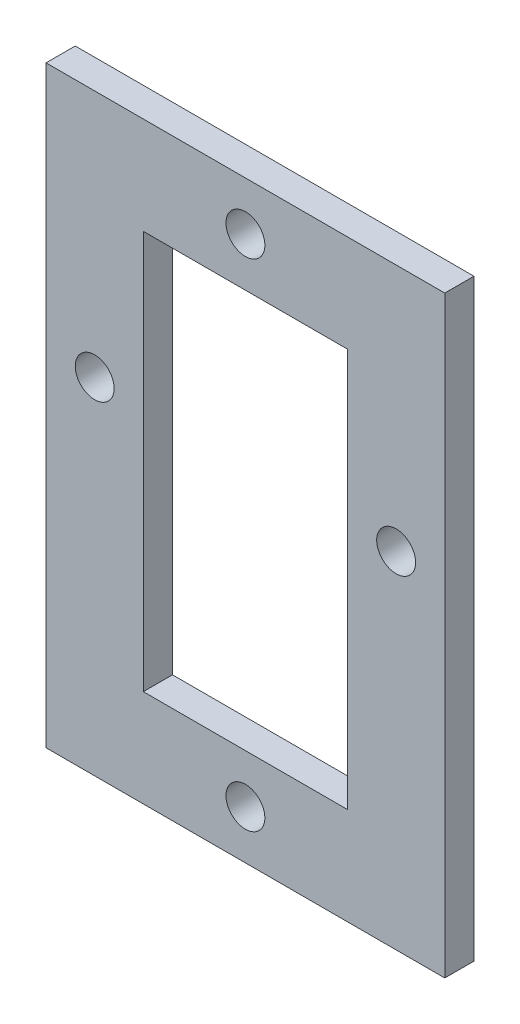
SolidWorks part; units mm, degrees
ref_plane "Front Plane" through (0, 0, 0) normal (0, 0, 1) x (1, 0, 0)
ref_plane "Top Plane" through (0, 0, 0) normal (0, 1, 0) x (1, 0, 0)
ref_plane "Right Plane" through (0, 0, 0) normal (1, 0, 0) x (0, 0, -1)
sketch "Sketch1" plane through (0, 0, 0) normal (0, 0, 1) x (1, 0, 0)
  line L1 (0, 0) -> (41, 0)
  line L2 (0, 0) -> (0, -61)
  line L3 (0, -61) -> (41, -61)
  line L4 (41, 0) -> (41, -61)
  dimension "D1" = 61
  dimension "D2" = 41
extrude "Boss-Extrude1" add sketch "Sketch1" along normal blind 3
sketch "Sketch2" plane through (0, 0, 3) normal (0, 0, 1) x (1, 0, 0)
  line L0 (0, -61) -> (41, -61) construction
  line L1 (10, -10) -> (31, -10)
  line L2 (10, -10) -> (10, -51)
  line L3 (10, -51) -> (31, -51)
  line L4 (31, -10) -> (31, -51)
  line L5 (10, -10) -> (31, -51) construction
  line L6 (10, -51) -> (31, -10) construction
  line L7 (41, -61) -> (41, 0) construction
  point P0 (20.5, -30.5)
  dimension "D1" = 21
  dimension "D2" = 41
  dimension "D3" = 10
  dimension "D4" = 10
extrude "Cut-Extrude1" cut sketch "Sketch2" against normal blind 3
sketch "Sketch3" plane through (0, 0, 3) normal (0, 0, 1) x (1, 0, 0)
  line L0 (0, 0) -> (0, -61) construction
  line L1 (41, -61) -> (41, 0) construction
  line L2 (41, 0) -> (0, 0) construction
  circle A0 centre (36, -25.5) radius 2
  circle A1 centre (5, -25.5) radius 2
  dimension "D1" = 4
  dimension "D2" = 4
  dimension "D3" = 5
  dimension "D4" = 5
  dimension "D6" = 25.5
  dimension "D5" = 25.5
extrude "Cut-Extrude2" cut sketch "Sketch3" against normal blind 3
sketch "Sketch4" plane through (0, 0, 3) normal (0, 0, 1) x (1, 0, 0)
  line L0 (31, -10) -> (10, -10) construction
  line L1 (10, -51) -> (31, -51) construction
  line L2 (41, -61) -> (41, 0) construction
  circle A0 centre (20.5, -5) radius 2
  circle A1 centre (20.5, -56) radius 2
  dimension "D1" = 4
  dimension "D2" = 4
  dimension "D3" = 5
  dimension "D4" = 5
  dimension "D5" = 20.5
  dimension "D6" = 20.5
extrude "Cut-Extrude3" cut sketch "Sketch4" against normal blind 10
